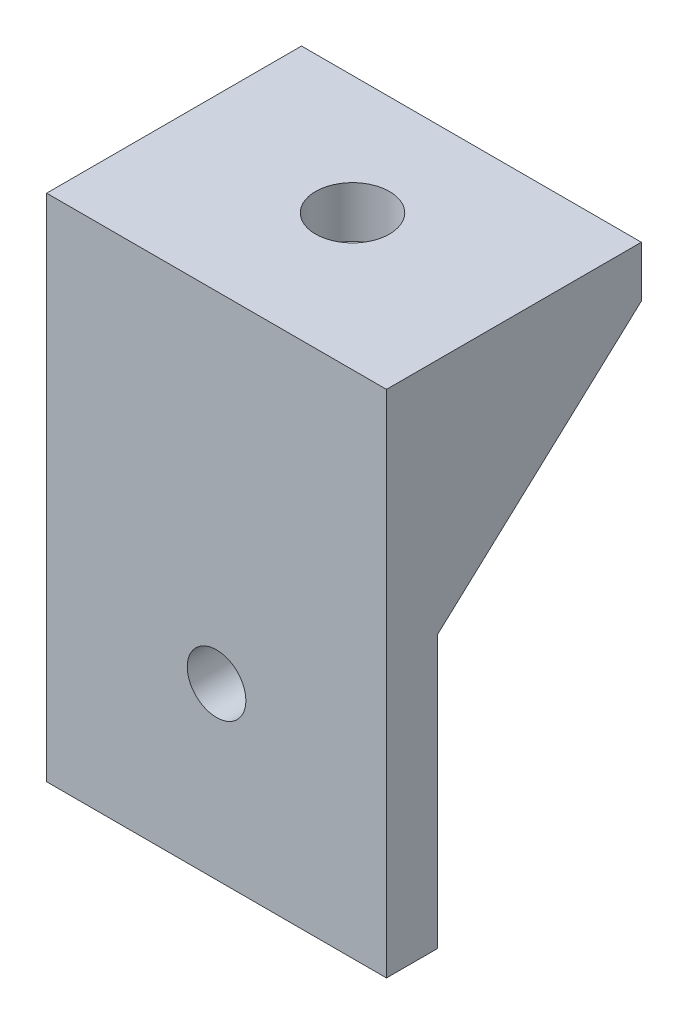
SolidWorks part; units mm, degrees
ref_plane "Front Plane" through (0, 0, 0) normal (0, 0, 1) x (1, 0, 0)
ref_plane "Top Plane" through (0, 0, 0) normal (0, 1, 0) x (1, 0, 0)
ref_plane "Right Plane" through (0, 0, 0) normal (1, 0, 0) x (0, 0, -1)
sketch "Sketch1" plane through (0, 0, 0) normal (0, 0, 1) x (1, 0, 0)
  line L1 (-4.7771, 26.7197) -> (15.2229, 26.7197)
  line L2 (-4.7771, 26.7197) -> (-4.7771, -3.2803)
  line L3 (-4.7771, -3.2803) -> (15.2229, -3.2803)
  line L4 (15.2229, 26.7197) -> (15.2229, -3.2803)
  dimension "D1" = 20
  dimension "D2" = 30
extrude "Boss-Extrude1" add sketch "Sketch1" along normal blind 3
sketch "Sketch2" plane through (0, 0, 0) normal (0, 0, -1) x (-1, 0, 0)
  line L0 (4.7771, 26.7197) -> (4.7771, -3.2803) construction
  line L1 (-15.2229, 26.7197) -> (4.7771, 26.7197)
  line L2 (-15.2229, 26.7197) -> (-15.2229, 23.7197)
  line L3 (-15.2229, 23.7197) -> (4.7771, 23.7197)
  line L4 (4.7771, 26.7197) -> (4.7771, 23.7197)
  dimension "D1" = 3
extrude "Boss-Extrude2" add sketch "Sketch2" along normal blind 12
sketch "Sketch3" plane through (0, 26.7197, 0) normal (0, 1, 0) x (1, 0, 0)
  line L1 (-4.7771, -3) -> (-4.7771, 12) construction
  line L4 (-4.7771, 12) -> (15.2229, 12) construction
  circle A0 centre (5.2229, 5) radius 2.175
  dimension "D1" = 10
  dimension "D2" = 7
  dimension "D3" = 4.35
extrude "Cut-Extrude1" cut sketch "Sketch3" against normal blind 12
sketch "Sketch5" plane through (0, 0, 0) normal (0, 0, -1) x (-1, 0, 0)
  line L0 (4.7771, 23.7197) -> (4.7771, -3.2803) construction
  line L1 (4.7771, -3.2803) -> (-15.2229, -3.2803) construction
  circle A0 centre (-5.2229, 6.7197) radius 1.725
  dimension "D1" = 10
  dimension "D2" = 3.45
  dimension "D3" = 10
extrude "Cut-Extrude2" cut sketch "Sketch5" against normal blind 12 contours A0
sketch "Sketch6" plane through (-4.7771, 0, 0) normal (-1, 0, 0) x (0, 0, 1)
  line L0 (-12, 23.7197) -> (0, 23.7197)
  line L1 (0, 23.7197) -> (0, 12.7197)
  line L2 (0, 23.7197) -> (0, -3.2803) construction
  line L3 (0, 12.7197) -> (-12, 23.7197)
  dimension "D1" = 11
extrude "Boss-Extrude3" add sketch "Sketch6" against normal blind 2
ref_plane "Plane2" through (5.2229, 0, 0) normal (-1, 0, 0) x (0, 0, 1)
mirror "Mirror1" about plane through (5.2229, 0, 0) normal (-1, 0, 0) of "Boss-Extrude3"
